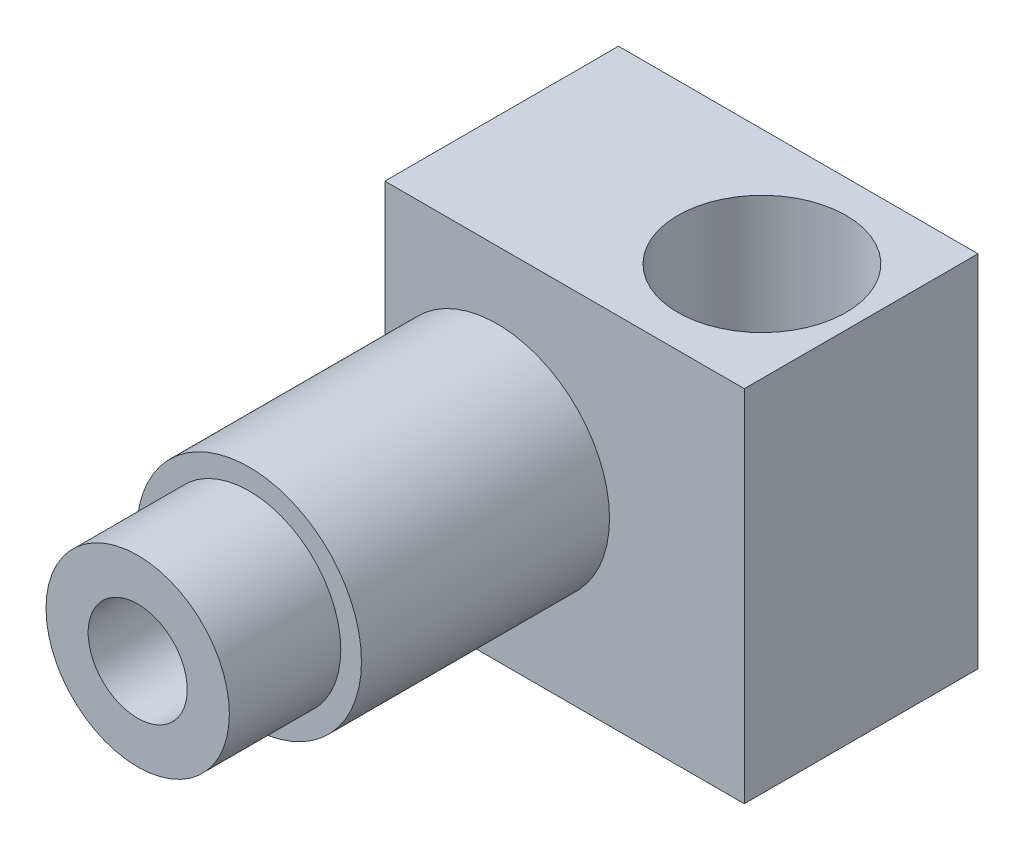
SolidWorks part; units mm, degrees
material "Brass"
ref_plane "Front" through (0, 0, 0) normal (0, 0, 1) x (1, 0, 0)
ref_plane "Top" through (0, 0, 0) normal (0, 1, 0) x (1, 0, 0)
ref_plane "Right" through (0, 0, 0) normal (1, 0, 0) x (0, 0, -1)
sketch "Sketch1" plane through (0, 0, 0) normal (0, 0, 1) x (1, 0, 0)
  line L1 (-6.35, -6.35) -> (6.35, -6.35)
  line L2 (-6.35, -6.35) -> (-6.35, 6.35)
  line L3 (-6.35, 6.35) -> (6.35, 6.35)
  line L4 (6.35, -6.35) -> (6.35, 6.35)
  line L5 (-6.35, -6.35) -> (6.35, 6.35) construction
  line L6 (-6.35, 6.35) -> (6.35, -6.35) construction
  point P0 (0, 0)
  dimension "D1" = 12.7
extrude "Boss-Extrude1" add sketch "Sketch1" along normal mid plane 8.255
sketch "Sketch2" plane through (0, -6.35, 0) normal (0, -1, 0) x (1, 0, 0)
  line L0 (6.35, 4.1275) -> (6.35, -4.1275) construction
  circle A0 centre (2.8448, 0) radius 2.9718
  dimension "D1" = 5.9436
  dimension "D2" = 3.5052
extrude "Cut-Extrude1" cut sketch "Sketch2" against normal through all
sketch "Sketch3" plane through (0, 0, 4.1275) normal (0, 0, 1) x (1, 0, 0)
  line L0 (-6.35, 6.35) -> (-6.35, -6.35) construction
  line L1 (6.35, 6.35) -> (-6.35, 6.35) construction
  circle A0 centre (-2.3812, 0) radius 3.9688
  dimension "D1" = 7.9375
  dimension "D2" = 6.35
extrude "Boss-Extrude2" add sketch "Sketch3" along normal blind 12.7
sketch "Sketch4" plane through (0, 0, 16.8275) normal (0, 0, 1) x (1, 0, 0)
  circle A0 centre (-2.3812, 0) radius 3.2385
  dimension "D1" = 6.477
extrude "Cut-Extrude2" cut sketch "Sketch4" against normal blind 3.937 flip side to cut
sketch "Sketch5" plane through (0, 0, -4.1275) normal (0, 0, -1) x (-1, 0, 0)
  line L0 (6.35, 6.35) -> (6.35, -6.35) construction
  circle A0 centre (2.3812, 0) radius 3.9688
  dimension "D1" = 7.9375
extrude "Boss-Extrude3" add sketch "Sketch5" along normal blind 3.048
chamfer "Chamfer1" distance 1.75 angle 60 1 edges at (-6.35, 0, -7.1755)
sketch "Sketch6" plane through (0, 0, -7.1755) normal (0, 0, -1) x (-1, 0, 0)
  circle A0 centre (2.3812, 0) radius 0.175
  dimension "D1" = 0.35
extrude "Cut-Extrude3" cut sketch "Sketch6" against normal through all
hole_wizard "Ø3.5 (3.5) Diameter Hole1" positions "Sketch8" profile "Sketch7" hole size "Ø3.5" standard "ANSI Metric"
sketch "Sketch8" plane through (0, 0, 16.8275) normal (0, 0, 1) x (1, 0, 0)
  point P0 (-2.3812, 0)
sketch "Sketch7" plane through (-2.3812, 0, 16.8275) normal (1, 0, 0) x (0, -1, 0)
  line L0 (0, 0) -> (0, 22.0515)
  line L1 (0, 22.0515) -> (1.75, 21)
  line L2 (1.75, 21) -> (1.75, 0)
  line L5 (1.75, 0) -> (0, 0)
  line L10 (0, 22.0515) -> (-1.75, 21) construction
  line L11 (0, -6.35) -> (0, 107.95) construction
  dimension "Hole Dia." = 3.5
  dimension "Hole Depth" = 21
  dimension "Drill Angle" = 118
sketch "Sketch11" plane through (-6.35, 0, 0) normal (-1, 0, 0) x (0, 0, 1)
  line L0 (4.1275, 6.35) -> (-4.1275, 6.35) construction
  line L1 (4.1275, 6.35) -> (4.1275, 0) construction
  circle A0 centre (-0.8725, 4.35) radius 1.143
  dimension "D1" = 2.286
  dimension "D2" = 2
  dimension "D3" = 5
extrude "Cut-Extrude4" cut sketch "Sketch11" against normal blind 4
